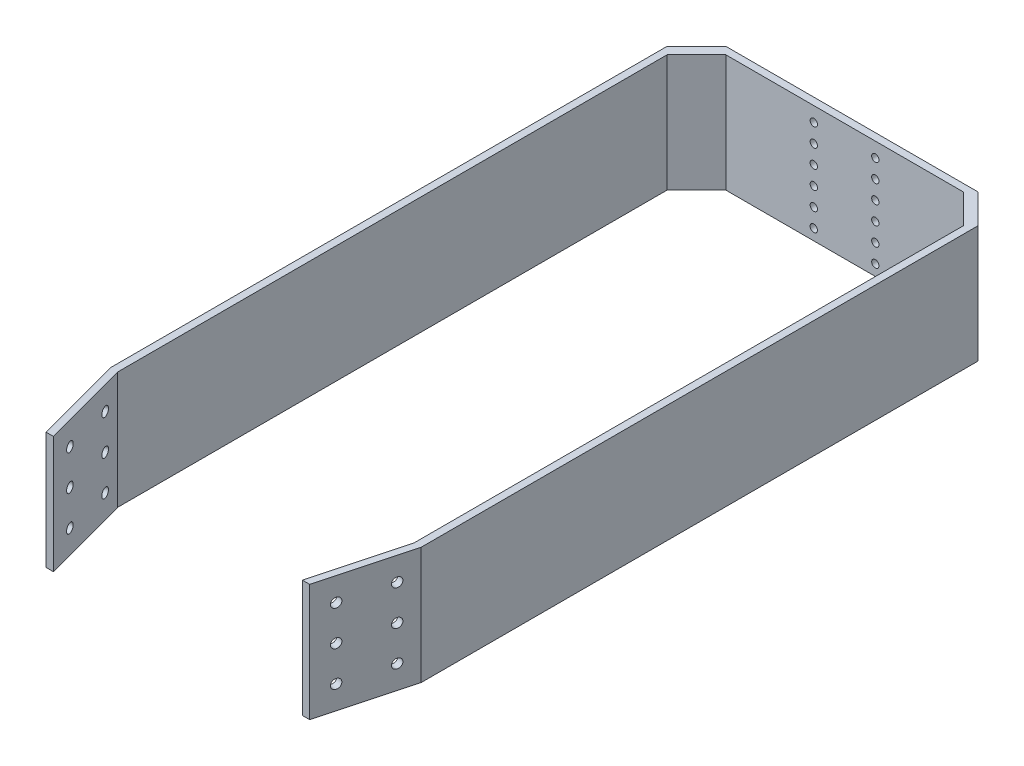
SolidWorks part; units mm, degrees
ref_plane "Front Plane" through (0, 0, 0) normal (0, 0, 1) x (1, 0, 0)
ref_plane "Top Plane" through (0, 0, 0) normal (0, 1, 0) x (1, 0, 0)
ref_plane "Right Plane" through (0, 0, 0) normal (1, 0, 0) x (0, 0, -1)
sketch "Sketch1" plane through (0, 0, 0) normal (0, 1, 0) x (1, 0, 0)
  line L0 (-45, -230) -> (-53.0385, -200)
  line L2 (53.0385, -200) -> (45, -230)
  line L3 (45, -230) -> (42.5, -230)
  line L4 (42.5, -230) -> (50.5385, -200)
  line L5 (50.5385, -200) -> (-50.5385, -200) construction
  line L6 (-50.5385, -200) -> (-42.5, -230)
  line L7 (-42.5, -230) -> (-45, -230)
  line L8 (0, 0) -> (0, -2.5) construction
  line L9 (-53.0385, -200) -> (-53.0385, 0)
  line L10 (-53.0385, 0) -> (53.0385, 0)
  line L11 (53.0385, 0) -> (53.0385, -200)
  line L12 (-50.5385, -200) -> (-50.5385, -2.5)
  line L13 (-50.5385, -2.5) -> (50.5385, -2.5)
  line L14 (50.5385, -2.5) -> (50.5385, -200)
  line L15 (-53.0385, -200) -> (-50.5385, -200) construction
  dimension "D1" = 2.5
  dimension "D2" = 85
  dimension "D3" = 105
  dimension "D4" = 30
  dimension "D5" = 230
extrude "Boss-Extrude1" add sketch "Sketch1" along normal blind 40
sketch "Sketch2" plane through (-99.4856, 0, 26.6571) normal (-0.9659, 0, 0.2588) x (0.2588, 0, 0.9659)
  line L0 (186.1578, 32) -> (186.1578, 8) construction
  line L1 (187.7578, 32) -> (187.7578, 8) construction
  line L2 (184.5578, 32) -> (184.5578, 8) construction
  line L3 (203.1578, 32) -> (203.1578, 8) construction
  line L4 (204.7578, 32) -> (204.7578, 8) construction
  line L5 (201.5578, 32) -> (201.5578, 8) construction
  line L6 (179.4578, 40) -> (179.4578, 0) construction
  line L7 (179.4578, 40) -> (210.5161, 40) construction
  line L8 (186.1578, 32) -> (186.1578, 40) construction
  line L9 (186.1578, 8) -> (186.1578, 0) construction
  line L10 (179.4578, 0) -> (210.5161, 0) construction
  arc A0 (187.7578, 32) -> (184.5578, 32) centre (186.1578, 32) ccw construction
  arc A1 (184.5578, 8) -> (187.7578, 8) centre (186.1578, 8) ccw construction
  arc A2 (204.7578, 32) -> (201.5578, 32) centre (203.1578, 32) ccw construction
  arc A3 (201.5578, 8) -> (204.7578, 8) centre (203.1578, 8) ccw construction
  circle A4 centre (186.1578, 32) radius 1.6
  circle A5 centre (186.1578, 8) radius 1.6
  circle A6 centre (203.1578, 8) radius 1.6
  circle A7 centre (203.1578, 32) radius 1.6
  circle A8 centre (203.1578, 20) radius 1.6
  circle A9 centre (186.1578, 20) radius 1.6
  point P2 (186.1578, 20)
  point P7 (203.1578, 20)
  dimension "D1" = 5.1
  dimension "D2" = 17
  dimension "D3" = 3.2
  dimension "D4" = 8
extrude "Cut-Extrude1" cut sketch "Sketch2" against normal up to next
mirror "Mirror1" about plane through (0, 0, 0) normal (1, 0, 0) of "Cut-Extrude1"
sketch "Sketch3" plane through (0, 0, 0) normal (0, 0, -1) x (-1, 0, 0)
  line L1 (-10.5, 35) -> (10.5, 35) construction
  line L4 (-53.0385, 40) -> (53.0385, 40) construction
  circle A0 centre (-10.5, 35) radius 1.25
  circle A2 centre (10.5, 35) radius 1.25
  point P9 (0, 35)
  dimension "D2" = 2.5
  dimension "D1" = 21
  dimension "D4" = 5
extrude "Cut-Extrude2" cut sketch "Sketch3" against normal up to next
pattern_linear "LPattern1" count 6 spacing 6.25 along (0, -1, 0) of "Cut-Extrude2"
chamfer "Chamfer1" distance 10 angle 45 4 edges at (53.0385, 20, 0) (50.5385, 20, 2.5) (-50.5385, 20, 2.5) (-53.0385, 20, 0)
